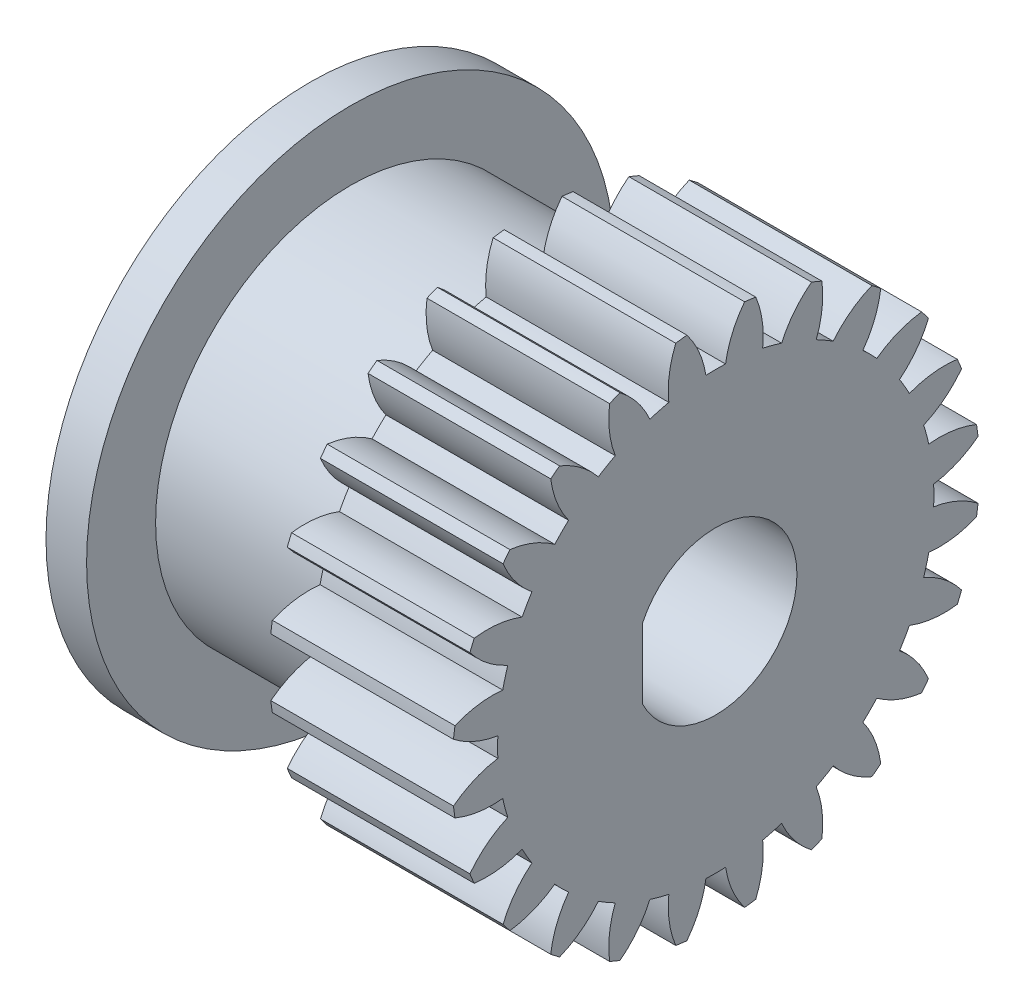
SolidWorks part; units mm, degrees
ref_plane "Plane1" through (0, 0, 0) normal (0, 0, 1) x (1, 0, 0)
ref_plane "Plane2" through (0, 0, 0) normal (0, 1, 0) x (1, 0, 0)
ref_plane "Plane3" through (0, 0, 0) normal (1, 0, 0) x (0, 0, -1)
sketch "HoldingSke" plane through (0, 0, 0) normal (0, 1, 0) x (1, 0, 0)
  line L0 (0, 0) -> (1.8271, -0.8135)
  line L1 (-15, 0) -> (100, 0) construction
  line L2 (0, 0) -> (-2.1039, 2.3779)
  line L3 (0, 0) -> (-11.863, 4.5341)
  line L4 (0, 0) -> (7.8894, 3.5126)
  line L5 (0, 0) -> (-46.8476, -17.4728)
  line L6 (0, 0) -> (-3.3159, -2.2372)
  line L7 (-2.1039, 2.3779) -> (8.6586, 51.2059)
  line L8 (-76.2, 54.61) -> (-75.7, 54.61)
  line L9 (-71.009, 38.7566) -> (-53.1078, 45.2721)
  line L10 (-76.2, 71.12) -> (104.1128, 71.12)
  line L11 (0, 0) -> (-4, 0)
  line L12 (-76.2, 101.6) -> (-76.181, 101.6)
  line L13 (24.9733, 27.94) -> (52.9518, 28.4284)
  line L14 (24.9733, 27.94) -> (24.9743, 27.94)
  line L15 (24.9733, 27.94) -> (100.4006, 29.5858)
  line L16 (-63.627, -0.5) -> (-12.827, -0.5)
  circle A0 centre (0, 0) radius 1.5
  circle A1 centre (0, 0) radius 5.374
  circle A2 centre (0, 0) radius 37.5
  circle A3 centre (0, 0) radius 1.5
  dimension "MHD" = 10.748
  dimension "Hub_dia" = 75
  dimension "Bore" = 3
  dimension "MBD" = 3
  dimension "Num_teeth" = 24
  dimension "Pitch" = 2
  dimension "Overall_len" = 50
  dimension "Show_teeth" = 24
  dimension "Thickness" = 4
  dimension "OAL" = 50.0001
  dimension "T_dim" = 0.5
  dimension "Ap" = 20
  dimension "H" = 19.05
  dimension "Pitch_radius" = 180.3128
  dimension "Width" = 4
  dimension "Backlash" = 0.019
  dimension "Addendum_fac" = 1
  dimension "Dedendum_fac" = 1.25
  dimension "Clearance_fac" = 0.25
  dimension "Dedendum_add" = 0.001
  dimension "Module" = 0.5
sketch "BasProSke" plane through (0, 0, 0) normal (0, 1, 0) x (1, 0, 0)
  line L0 (-10, 0) -> (60, 0) construction
  line L1 (0, 0) -> (0, 6.5)
  line L2 (0, 0) -> (4.5, 0)
  line L3 (4.5, 0) -> (4.5, 6.5)
  line L4 (4.5, 6.5) -> (0, 6.5)
  dimension "Thickness" = 4.5
  dimension "Diameter" = 13
revolve "Base-Revolve" add sketch "BasProSke" angle 360 about L0
sketch "TooCutSke" plane through (0, 0, 0) normal (1, 0, 0) x (0, 0, -1)
  line L1 (0, 0) -> (0, 107) construction
  line L2 (0, 0) -> (-0.4257, 5.9849) construction
  line L3 (0, 0) -> (-1.5635, 11.876) construction
  line L4 (-0.4257, 5.9849) -> (-0.7818, 5.938) construction
  arc A0 (0.2416, 5.3686) -> (-0.2416, 5.3686) centre (0, 0) ccw
  arc A1 (0.7297, 6.4845) -> (-0.7297, 6.4845) centre (0, 0) ccw
  circle A2 centre (0, 0) radius 6 construction
  circle A3 centre (0, 0) radius 5.6382 construction
  arc A4 (-0.2416, 5.3686) -> (-0.7297, 6.4845) centre (-2.6126, 4.9963) ccw
  arc A5 (0.7297, 6.4845) -> (0.2416, 5.3686) centre (2.6126, 4.9963) ccw
  dimension "Root_dia" = 10.748
  dimension "Overcut_dia" = 13.0508
  dimension "Pitch_dia" = 12
  dimension "Base_dia" = 11.2763
  dimension "Flank_rad" = 2.4
  dimension "Half_ang" = 7.5
  dimension "Half_CT" = 0.3592
extrude "ToothCut" cut sketch "TooCutSke" along normal through all
fillet "Breaks" [suppressed] radius 0.01
fillet "RootFillets" [suppressed] radius 0.126
pattern_circular "TeethCuts" count 24 every 15 about axis through (-10, 0, 0) along (1, 0, 0) of "ToothCut", "RootFillets", "Breaks"
sketch "HubNeaOneSke" plane through (0, 0, 0) normal (-1, 0, 0) x (0, 0, 1)
  circle A0 centre (0, 0) radius 5.374
  dimension "Diameter" = 10.748
extrude "HubNearOne" [suppressed] add sketch "HubNeaOneSke" along normal blind 45.5001
sketch "HubNeaBotSke" plane through (0, 0, 0) normal (-1, 0, 0) x (0, 0, 1)
  circle A0 centre (0, 0) radius 5.374
  dimension "Diameter" = 10.748
extrude "HubNearBoth" [suppressed] add sketch "HubNeaBotSke" along normal blind 22.75
ref_plane "FarPln" through (4.5, 0, 0) normal (1, 0, 0) x (0, 0, -1)
sketch "HubFarSke" plane through (4.5, 0, 0) normal (1, 0, 0) x (0, 0, -1)
  circle A0 centre (0, 0) radius 5.374
  dimension "Diameter" = 10.748
extrude "HubFar" [suppressed] add sketch "HubFarSke" along normal blind 22.75
sketch "BorSke" plane through (0, 0, 0) normal (1, 0, 0) x (0, 0, -1)
  circle A0 centre (0, 0) radius 1.5
  dimension "Diameter" = 3
extrude "Bore" cut sketch "BorSke" along normal mid plane 100.0001
sketch "KeySke" plane through (0, 0, 0) normal (1, 0, 0) x (0, 0, -1)
  line L0 (-0.6, 0) -> (-0.6, 2)
  line L1 (-0.6, 2) -> (0.6, 2)
  line L2 (0.6, 2) -> (0.6, 0)
  line L3 (0, 0) -> (0, 34) construction
  line L4 (-0.6, 0) -> (0.6, 0)
  dimension "Offset" = 2
  dimension "Width" = 1.2
extrude "Keyway" [suppressed] cut sketch "KeySke" along normal mid plane 100.0001
pattern_circular "Keyway2" [suppressed] count 2 every 90 about axis through (-10, 0, 0) along (1, 0, 0)
sketch "草图1" plane through (0, 0, 0) normal (-1, 0, 0) x (0, 0, 1)
  circle A0 centre (0, 0) radius 4.8
  circle A1 centre (0, 0) radius 1.5
extrude "凸台-拉伸1" add sketch "草图1" along normal blind 4.5
sketch "草图2" plane through (-4.5, 0, 0) normal (-1, 0, 0) x (0, 0, 1)
  circle A0 centre (0, 0) radius 1.5
  circle A1 centre (0, 0) radius 6.5
extrude "凸台-拉伸2" add sketch "草图2" along normal blind 1
sketch "草图3" plane through (-5.5, 0, 0) normal (-1, 0, 0) x (0, 0, 1)
  line L0 (1.8, -0.8718) -> (1.8, 0.8718)
  arc A0 (1.8, 0.8718) -> (1.8, -0.8718) centre (0, 0) ccw
extrude "切除-拉伸1" cut sketch "草图3" against normal up to next
equation "' \"Module@HoldingSke\" = 6.35"
equation "' \"Num_teeth@HoldingSke\" = 12"
equation "' \"Ap@HoldingSke\" =  20"
equation "' \"Ap@HoldingSke\" = 20"
equation "' \"Width@HoldingSke\" = 0.5 * 25.4"
equation "' \"Hub_dia@HoldingSke\"= 1 * 25.4"
equation "' \"Hub_dia@HoldingSke\" = 1 * 25.4"
equation "' \"Overall_len@HoldingSke\" = 1.0 * 25.4"
equation "' \"Bore@HoldingSke\" = 0.75 * 25.4"
equation "' \"T_dim@HoldingSke\" = 0.1 * 25.4"
equation "' \"Width@KeySke\" = 0.25 * 25.4"
equation "' \"Show_teeth@HoldingSke\" = 13"
equation "' \"Backlash@HoldingSke\" = 0.009 * 25.4"
equation "' \"Addendum_fac@HoldingSke\" = 1.0"
equation "' \"Dedendum_fac@HoldingSke\" = 1.25"
equation "' \"Dedendum_add@HoldingSke\" = 0.00005 * 25.4"
equation "' \"Clearance_fac@HoldingSke\" = 0.25"
equation "\"Pitch@HoldingSke\" = 1 / \"Module@HoldingSke\""
equation "\"Overcut_dia@TooCutSke\" = (\"Num_teeth@HoldingSke\" + 2 * \"Addendum_fac@HoldingSke\") / \"Pitch@HoldingSke\" + 0.002 * 25.4"
equation "\"Pitch_dia@TooCutSke\" = \"Num_teeth@HoldingSke\" / \"Pitch@HoldingSke\""
equation "\"Base_dia@TooCutSke\" = \"Num_teeth@HoldingSke\" / \"Pitch@HoldingSke\" * cos((\"Ap@HoldingSke\"  * 3.14159265 / 180))"
equation "\"Root_dia@TooCutSke\" = (\"Num_teeth@HoldingSke\" + 2) / \"Pitch@HoldingSke\" - 2 * (\"Addendum_fac@HoldingSke\" + \"Dedendum_fac@HoldingSke\") / \"Pitch@HoldingSke\" - \"Dedendum_add@HoldingSke\" * 2"
equation "\"Half_ang@TooCutSke\" = 180 / \"Num_teeth@HoldingSke\""
equation "\"Half_CT@TooCutSke\" = \"Num_teeth@HoldingSke\" / \"Pitch@HoldingSke\" * sin((3.14159265 / 2 / \"Num_teeth@HoldingSke\")) / 2 - 7 * \"Backlash@HoldingSke\" / 4"
equation "\"Flank_rad@TooCutSke\" = \"Num_teeth@HoldingSke\" / \"Pitch@HoldingSke\" / 5"
equation "\"Radius@RootFillets\" = \"Clearance_fac@HoldingSke\" / \"Pitch@HoldingSke\" + \"Dedendum_add@HoldingSke\""
equation "\"Break_rad@Breaks\" = 0.02 / \"Pitch@HoldingSke\""
equation "\"Thickness@HoldingSke\" = \"Width@HoldingSke\""
equation "\"OAL@HoldingSke\" = \"Thickness@HoldingSke\""
equation "\"MHD@HoldingSke\" = (\"Num_teeth@HoldingSke\" + 2) / \"Pitch@HoldingSke\" - 2 * (\"Addendum_fac@HoldingSke\" + \"Dedendum_fac@HoldingSke\")  / \"Pitch@HoldingSke\" - \"Dedendum_add@HoldingSke\" * 2"
equation "\"MBD@HoldingSke\" = (\"Num_teeth@HoldingSke\" + 2) / \"Pitch@HoldingSke\" - 2 * (\"Addendum_fac@HoldingSke\" + \"Dedendum_fac@HoldingSke\")  / \"Pitch@HoldingSke\" - \"Dedendum_add@HoldingSke\" * 2 - 0.002 * 25.4"
equation "\"MHD@HoldingSke\" = ((sgn( \"MHD@HoldingSke\" - \"Hub_dia@HoldingSke\" )-1)*( \"MHD@HoldingSke\" - \"Hub_dia@HoldingSke\" ))/-2+ \"Hub_dia@HoldingSke\""
equation "\"MBD@HoldingSke\" = ((sgn( \"MBD@HoldingSke\" - \"Bore@HoldingSke\" )-1)*( \"MBD@HoldingSke\" - \"Bore@HoldingSke\" ))/-2+ \"Bore@HoldingSke\""
equation "\"OAL@HoldingSke\" = ((sgn( \"OAL@HoldingSke\" - \"Overall_len@HoldingSke\" )+1)*( \"OAL@HoldingSke\" - \"Overall_len@HoldingSke\" ))/2 + \"Overall_len@HoldingSke\" + 0.000002 * 25.4"
equation "\"Num_teeth@TeethCuts\" = int( \"Show_teeth@HoldingSke\" ) + 1"
equation "\"Num_teeth@TeethCuts\" = ((sgn( \"Num_teeth@TeethCuts\" - \"Num_teeth@HoldingSke\" )-1)*( \"Num_teeth@TeethCuts\" - \"Num_teeth@HoldingSke\" ))/-2+ \"Num_teeth@HoldingSke\""
equation "\"Num_teeth@TeethCuts\" = ((sgn( \"Num_teeth@TeethCuts\" - 2.0)+1)*( \"Num_teeth@TeethCuts\" - 2.0))/2 +2.0"
equation "\"Angle@TeethCuts\" = 360.0 / \"Num_teeth@HoldingSke\""
equation "\"Diameter@BasProSke\" = (\"Num_teeth@HoldingSke\" + 2 * \"Addendum_fac@HoldingSke\") / \"Pitch@HoldingSke\""
equation "' \"Fillet_rad@BasProSke\" =  \"Thickness@HoldingSke\" * 0.05"
equation "' \"Fillet_rad@BasProSke\" = \"Thickness@HoldingSke\" * 0.05"
equation "\"MHD@HoldingSke\" = ((sgn( \"MHD@HoldingSke\" - \"Root_dia@TooCutSke\" )-1)*( \"MHD@HoldingSke\" - \"Root_dia@TooCutSke\" ))/-2+ \"Root_dia@TooCutSke\""
equation "\"Diameter@HubNeaOneSke\" = \"MHD@HoldingSke\""
equation "\"Length@HubNearOne\" = \"OAL@HoldingSke\" - \"Thickness@BasProSke\""
equation "\"Diameter@HubNeaBotSke\" = \"MHD@HoldingSke\""
equation "\"Length@HubNearBoth\" = ( \"OAL@HoldingSke\" - \"Thickness@BasProSke\" ) / 2.0"
equation "\"Thickness@FarPln\" = \"Thickness@BasProSke\""
equation "\"Diameter@HubFarSke\" = \"MHD@HoldingSke\""
equation "\"Length@HubFar\" = ( \"OAL@HoldingSke\" - \"Thickness@BasProSke\" ) / 2.0"
equation "\"Diameter@BorSke\" = \"MBD@HoldingSke\""
equation "\"D1@Bore\" = \"OAL@HoldingSke\" * 2.0"
equation "\"D1@Keyway\" = \"OAL@HoldingSke\" * 2.0"
equation "\"Offset@KeySke\" = \"T_dim@HoldingSke\" + \"MBD@HoldingSke\" / 2.0"
